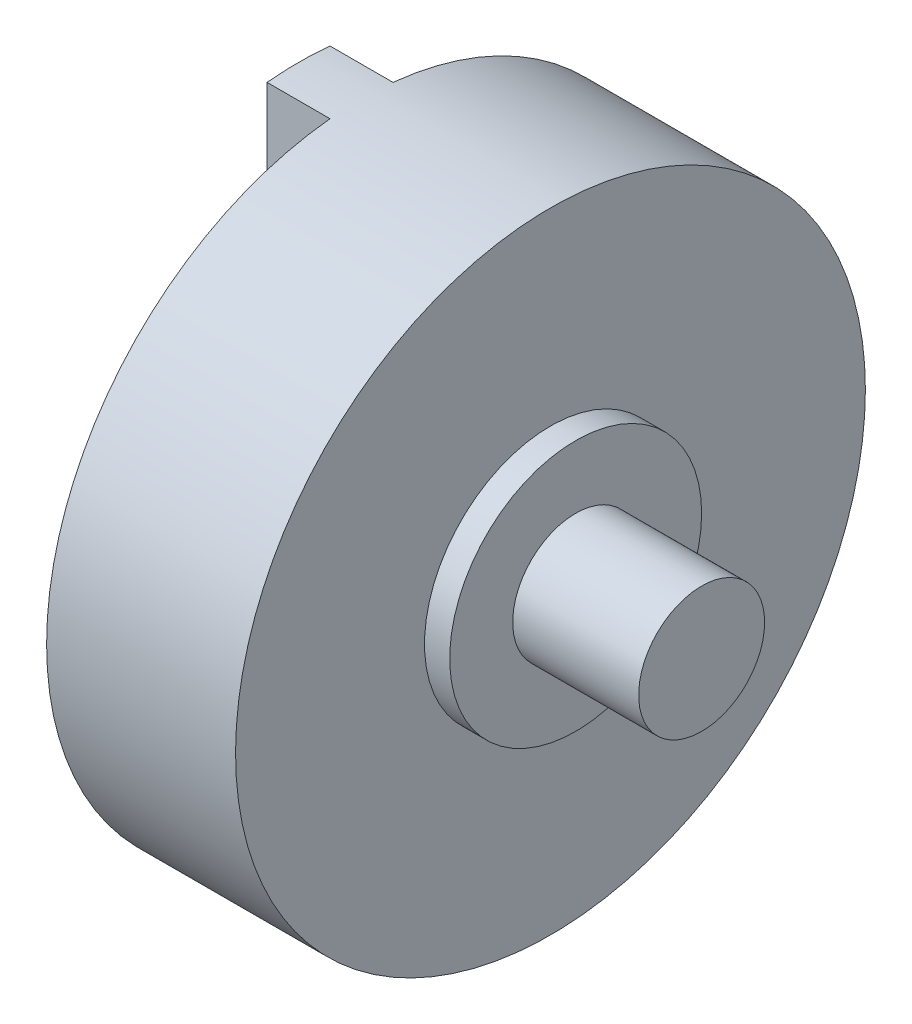
SolidWorks part; units mm, degrees
ref_plane "Front Plane" through (0, 0, 0) normal (0, 0, 1) x (1, 0, 0)
ref_plane "Top Plane" through (0, 0, 0) normal (0, 1, 0) x (1, 0, 0)
ref_plane "Right Plane" through (0, 0, 0) normal (1, 0, 0) x (0, 0, -1)
sketch "Sketch1" plane through (0, 0, 0) normal (1, 0, 0) x (0, 0, -1)
  circle A0 centre (0, 0) radius 25
  dimension "D1" = 50
extrude "Boss-Extrude1" add sketch "Sketch1" along normal mid plane 15
sketch "Sketch2" plane through (7.5, 0, 0) normal (1, 0, 0) x (0, 0, -1)
  circle A0 centre (0, 0) radius 5
  dimension "D1" = 10
extrude "Boss-Extrude2" add sketch "Sketch2" along normal blind 12
sketch "Sketch3" plane through (-7.5, 0, 0) normal (-1, 0, 0) x (0, 0, 1)
  line L2 (2.5, 24.8747) -> (2.5, -24.8747)
  line L4 (-2.5, 24.8747) -> (-2.5, -24.8747)
  line L5 (2.2216, 24.9011) -> (-2.2216, -24.9011) construction
  line L6 (2.2216, -24.9011) -> (-2.2216, 24.9011) construction
  circle A0 centre (0, 0) radius 25 construction
  arc A1 (-2.5, -24.8747) -> (2.5, -24.8747) centre (0, 0) ccw
  arc A2 (2.5, 24.8747) -> (-2.5, 24.8747) centre (0, 0) ccw
  point P0 (0, 0)
extrude "Boss-Extrude3" add sketch "Sketch3" along normal blind 5
sketch "Sketch4" plane through (7.5, 0, 0) normal (1, 0, 0) x (0, 0, -1)
  circle A0 centre (0, 0) radius 10
  dimension "D1" = 20
extrude "Boss-Extrude4" add sketch "Sketch4" along normal blind 2
